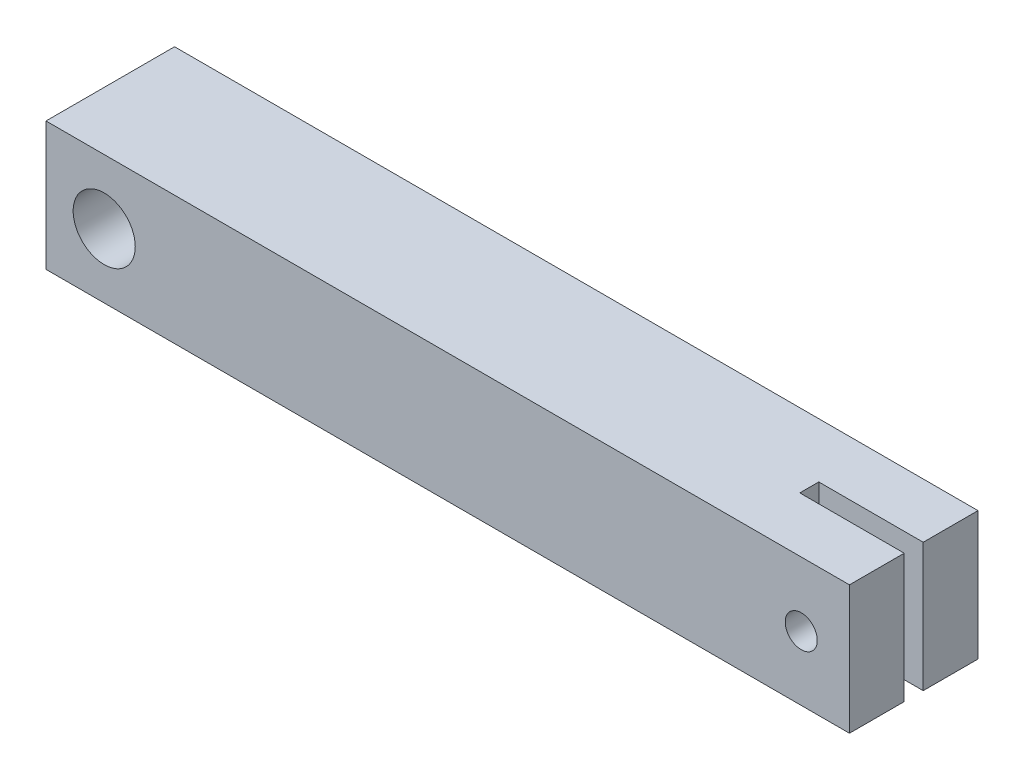
SolidWorks part; units mm, degrees
material "Fundición gris (SN)"
ref_plane "Alzado" through (0, 0, 0) normal (0, 0, 1) x (1, 0, 0)
ref_plane "Planta" through (0, 0, 0) normal (0, 1, 0) x (1, 0, 0)
ref_plane "Vista lateral" through (0, 0, 0) normal (1, 0, 0) x (0, 0, -1)
sketch "Croquis1" plane through (0, 0, 0) normal (0, 0, 1) x (1, 0, 0)
  line L1 (25, -4) -> (-25, -4)
  line L2 (25, -4) -> (25, 4)
  line L3 (25, 4) -> (-25, 4)
  line L4 (-25, -4) -> (-25, 4)
  line L5 (25, -4) -> (-25, 4) construction
  line L6 (25, 4) -> (-25, -4) construction
  circle A0 centre (-21.3778, 0) radius 1.9328
  circle A1 centre (22, 0) radius 0.9966
  point P0 (0, 0)
  dimension "D1" = 8
  dimension "D2" = 50
  dimension "D3" = 3
extrude "Saliente-Extruir1" add sketch "Croquis1" along normal mid plane 8
sketch "Croquis2" plane through (0, 4, 0) normal (0, 1, 0) x (1, 0, 0)
  line L0 (25, -4) -> (25, 4) construction
  line L1 (31.5, 0.5903) -> (18.5, 0.5903)
  line L2 (31.5, 0.5903) -> (31.5, -0.5903)
  line L3 (31.5, -0.5903) -> (18.5, -0.5903)
  line L4 (18.5, 0.5903) -> (18.5, -0.5903)
  line L5 (31.5, 0.5903) -> (18.5, -0.5903) construction
  line L6 (31.5, -0.5903) -> (18.5, 0.5903) construction
  point P0 (25, 0)
  dimension "D1" = 13
extrude "Cortar-Extruir1" cut sketch "Croquis2" against normal through all
